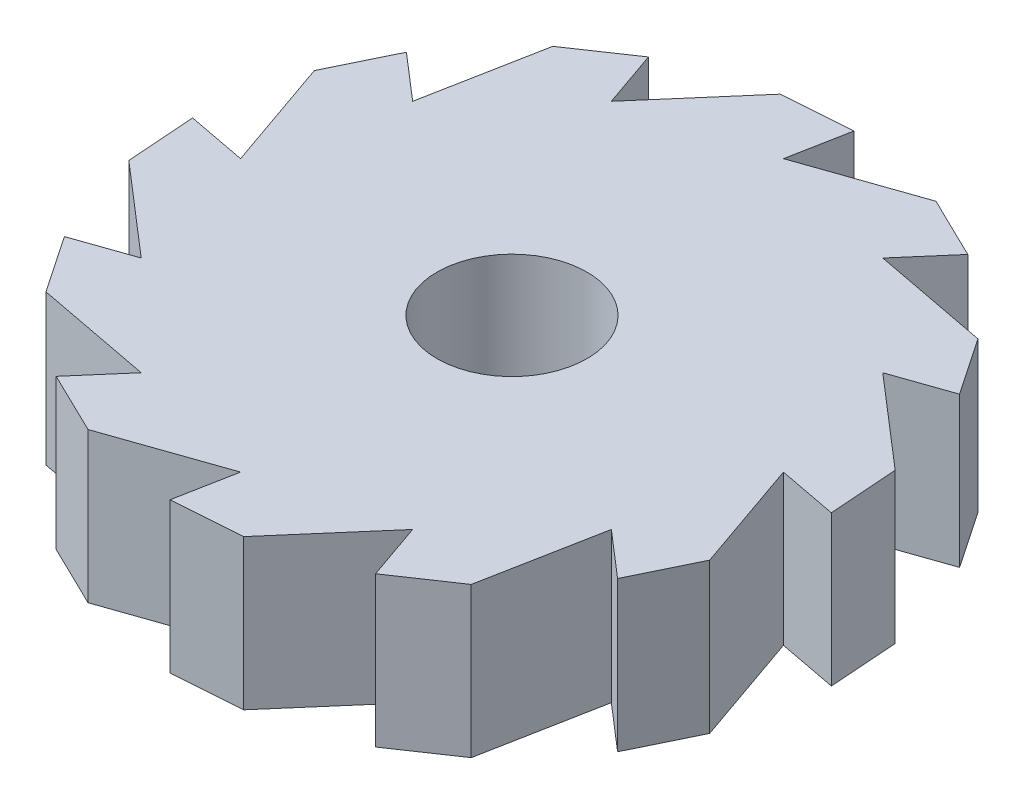
SolidWorks part; units mm, degrees
ref_plane "前视基准面" through (0, 0, 0) normal (0, 0, 1) x (1, 0, 0)
ref_plane "上视基准面" through (0, 0, 0) normal (0, 1, 0) x (1, 0, 0)
ref_plane "右视基准面" through (0, 0, 0) normal (1, 0, 0) x (0, 0, -1)
sketch "草图1" plane through (0, 0, 0) normal (0, 1, 0) x (1, 0, 0)
  line L0 (-25.036, 0) -> (20.7922, 0) construction
  line L1 (0, -20.331) -> (0, 23.329) construction
  line L2 (0, 18.0913) -> (7.54, 20.7166)
  line L3 (7.54, 20.7166) -> (11.6709, 18.7085)
  line L4 (11.6709, 18.7085) -> (9.0456, 15.6675)
  line L5 (9.0456, 15.6675) -> (0, 0) construction
  line L6 (9.0456, 15.6675) -> (16.8882, 14.1711)
  line L7 (16.8882, 14.1711) -> (19.4615, 10.3667)
  line L8 (19.4615, 10.3667) -> (15.6675, 9.0456)
  line L9 (15.6675, 9.0456) -> (21.7111, 3.8284)
  line L10 (21.7111, 3.8284) -> (22.0375, -0.753)
  line L11 (22.0375, -0.753) -> (18.0913, 0)
  line L12 (18.0913, 0) -> (20.7166, -7.54)
  line L13 (20.7166, -7.54) -> (18.7085, -11.6709)
  line L14 (18.7085, -11.6709) -> (15.6675, -9.0456)
  line L15 (15.6675, -9.0456) -> (14.1711, -16.8882)
  line L16 (14.1711, -16.8882) -> (10.3667, -19.4615)
  line L17 (10.3667, -19.4615) -> (9.0456, -15.6675)
  line L18 (9.0456, -15.6675) -> (3.8284, -21.7111)
  line L19 (3.8284, -21.7111) -> (-0.753, -22.0375)
  line L20 (-0.753, -22.0375) -> (0, -18.0913)
  line L21 (0, -18.0913) -> (-7.54, -20.7166)
  line L22 (-7.54, -20.7166) -> (-11.6709, -18.7085)
  line L23 (-11.6709, -18.7085) -> (-9.0456, -15.6675)
  line L24 (-9.0456, -15.6675) -> (-16.8882, -14.1711)
  line L25 (-16.8882, -14.1711) -> (-19.4615, -10.3667)
  line L26 (-19.4615, -10.3667) -> (-15.6675, -9.0456)
  line L27 (-15.6675, -9.0456) -> (-21.7111, -3.8284)
  line L28 (-21.7111, -3.8284) -> (-22.0375, 0.753)
  line L29 (-22.0375, 0.753) -> (-18.0913, 0)
  line L30 (-18.0913, 0) -> (-20.7166, 7.54)
  line L31 (-20.7166, 7.54) -> (-18.7085, 11.6709)
  line L32 (-18.7085, 11.6709) -> (-15.6675, 9.0456)
  line L33 (-15.6675, 9.0456) -> (-14.1711, 16.8882)
  line L34 (-14.1711, 16.8882) -> (-10.3667, 19.4615)
  line L35 (-10.3667, 19.4615) -> (-9.0456, 15.6675)
  line L36 (-9.0456, 15.6675) -> (-3.8284, 21.7111)
  line L37 (-3.8284, 21.7111) -> (0.753, 22.0375)
  line L38 (0.753, 22.0375) -> (0, 18.0913)
  circle A0 centre (0, 0) radius 5
  point P58 (0, 0)
  dimension "D1" = 30
  dimension "D3" = 10
  dimension "D4" = 2.6252
  dimension "D5" = 60
  dimension "D2" = 12
extrude "凸台-拉伸1" add sketch "草图1" along normal blind 10
